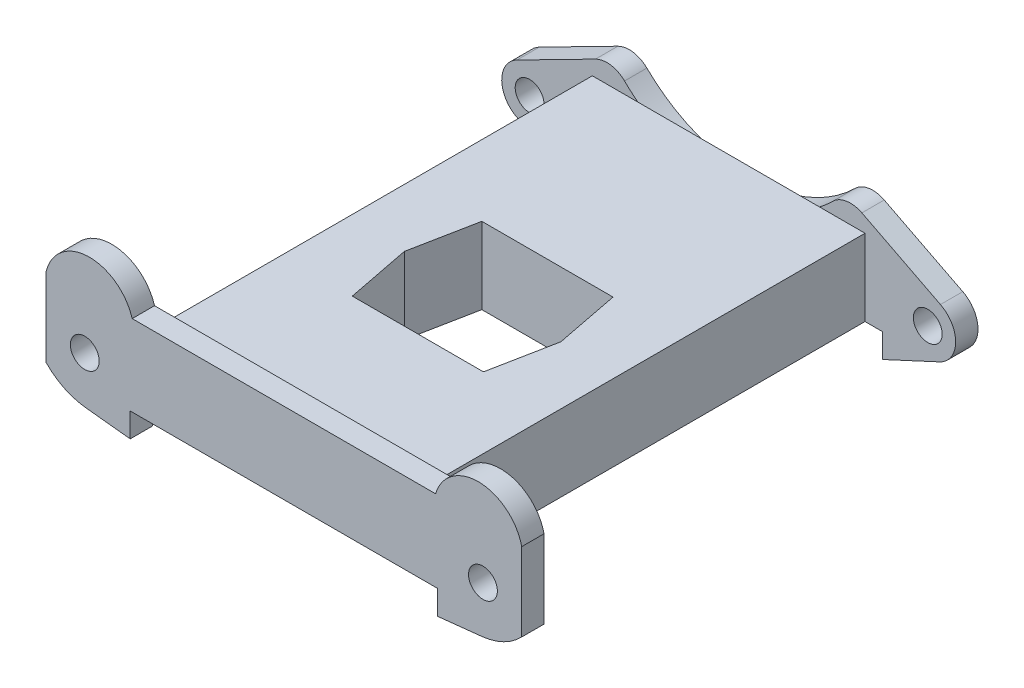
SolidWorks part; units mm, degrees
ref_plane "Front Plane" through (0, 0, 0) normal (0, 0, 1) x (1, 0, 0)
ref_plane "Top Plane" through (0, 0, 0) normal (0, 1, 0) x (1, 0, 0)
ref_plane "Right Plane" through (0, 0, 0) normal (1, 0, 0) x (0, 0, -1)
sketch "Sketch1" plane through (0, 0, 0) normal (0, 1, 0) x (1, 0, 0)
  line L0 (-8.9499, 4.0894) -> (8.9499, 4.0894)
  line L1 (18.6055, -28.829) -> (-18.6055, -28.829)
  line L2 (18.6055, -28.829) -> (18.6055, 28.829)
  line L3 (18.6055, 28.829) -> (-18.6055, 28.829)
  line L4 (-18.6055, -28.829) -> (-18.6055, 28.829)
  line L5 (18.6055, -28.829) -> (-18.6055, 28.829) construction
  line L6 (18.6055, 28.829) -> (-18.6055, -28.829) construction
  line L7 (8.9499, 4.0894) -> (10.6807, -4.7498)
  line L8 (10.6807, -4.7498) -> (8.9499, -13.589)
  line L9 (8.9499, -13.589) -> (-8.9499, -13.589)
  line L10 (-8.9499, -13.589) -> (-10.6807, -4.7498)
  line L11 (-10.6807, -4.7498) -> (-8.9499, 4.0894)
  line L12 (0, 4.0894) -> (0, -13.589) construction
  point P0 (0, 0)
  dimension "D1" = 57.658
  dimension "D2" = 37.211
  dimension "D3" = 21.3614
  dimension "D4" = 17.6784
  dimension "D5" = 15.24
  dimension "D6" = 9.0071
extrude "Boss-Extrude1" add sketch "Sketch1" along normal blind 10.4394
sketch "Sketch2" plane through (0, 0, 28.829) normal (0, 0, 1) x (1, 0, 0)
  line L0 (-20.701, 11.049) -> (20.701, 11.049)
  line L1 (-32.4612, 10.6796) -> (-32.4612, 0)
  line L2 (-20.9677, 0) -> (20.9677, 0)
  line L3 (-27.0496, -2.6515) -> (-20.9677, -3.302)
  line L4 (0, 14.523) -> (0, -4.1487) construction
  line L5 (20.9677, -3.302) -> (20.9677, 0)
  line L6 (-20.9677, -3.302) -> (-20.9677, 0)
  line L7 (27.0496, -2.6515) -> (20.9677, -3.302)
  line L8 (-18.6055, 0) -> (18.6055, 0) construction
  line L9 (32.4612, 10.6796) -> (32.4612, 0)
  arc A0 (-32.4612, 0) -> (-27.0496, -2.6515) centre (-26.1127, 6.1087) ccw
  arc A1 (20.701, 11.049) -> (32.4612, 10.6796) centre (26.5324, 9.3131) cw
  arc A2 (32.4612, 0) -> (27.0496, -2.6515) centre (26.1127, 6.1087) cw
  arc A4 (-20.701, 11.049) -> (-32.4612, 10.6796) centre (-26.5324, 9.3131) ccw
  point P3 (0, 11.049)
  point P7 (0, 0)
  point P13 (0, 11.049)
  point P15 (0, 0)
  point P19 (0, 11.049)
  point P26 (0, 11.049)
  dimension "D5" = 6.0843
  dimension "D8" = 8.8102
  dimension "D1" = 20.9677
  dimension "D2" = 32.4612
  dimension "D3" = 3.302
  dimension "D4" = 11.049
  dimension "D6" = 20.701
  dimension "D7" = 6.1166
  dimension "D9" = 10.6796
extrude "Boss-Extrude2" add sketch "Sketch2" along normal blind 3.048
sketch "Sketch3" plane through (0, 0, -28.829) normal (0, 0, -1) x (-1, 0, 0)
  line L0 (0, 6.223) -> (0, 0) construction
  line L1 (-18.6055, 0) -> (18.6055, 0) construction
  line L2 (18.175, 12.6299) -> (28.8986, 7.1591)
  line L3 (28.7697, 0.3147) -> (20.9677, -3.302)
  line L4 (20.9677, -3.302) -> (20.9677, 0)
  line L5 (20.9677, 0) -> (0, 0)
  line L6 (30.9753, 9.9955) -> (30.9753, -1.3561) construction
  line L7 (9.3185, 13.0048) -> (19.1089, 13.0048) construction
  line L8 (-9.3185, 13.0048) -> (-19.1089, 13.0048) construction
  line L9 (-30.9753, 9.9955) -> (-30.9753, -1.3561) construction
  line L10 (-20.9677, -3.302) -> (-20.9677, 0)
  line L11 (-28.7697, 0.3147) -> (-20.9677, -3.302)
  line L12 (-18.175, 12.6299) -> (-28.8986, 7.1591)
  line L13 (-20.9677, 0) -> (0, 0)
  arc A0 (-14.2133, 12.0244) -> (14.2133, 12.0244) centre (0, 26.5348) ccw
  arc A1 (28.8986, 7.1591) -> (28.7697, 0.3147) centre (27.1687, 3.7683) cw
  arc A2 (14.2133, 12.0244) -> (18.175, 12.6299) centre (16.6152, 9.5724) cw
  arc A3 (-14.2133, 12.0244) -> (-18.175, 12.6299) centre (-16.6152, 9.5724) ccw
  arc A4 (-28.8986, 7.1591) -> (-28.7697, 0.3147) centre (-27.1687, 3.7683) ccw
  dimension "D1" = 13.0048
  dimension "D4" = 30.9753
  dimension "D6" = 8.5995
extrude "Boss-Extrude3" add sketch "Sketch3" along normal blind 3.048
sketch "Sketch5" plane through (0, 0, -31.877) normal (0, 0, -1) x (-1, 0, 0)
  circle A0 centre (-27.1687, 3.7683) radius 1.9685
  circle A1 centre (27.1687, 3.7683) radius 1.9685
  arc A2 (-28.8986, 7.1591) -> (-28.7697, 0.3147) centre (-27.1687, 3.7683) ccw construction
  arc A3 (28.7697, 0.3147) -> (28.8986, 7.1591) centre (27.1687, 3.7683) ccw construction
  dimension "D2" = 3.937
extrude "Cut-Extrude1" cut sketch "Sketch5" against normal through all
sketch "Sketch6" plane through (0, 0, 0) normal (0, -1, 0) x (1, 0, 0)
  line L0 (0, 40.7775) -> (0, -39.818) construction
  line L1 (-20.9677, 31.877) -> (20.9677, 31.877) construction
  circle A0 centre (-10.0076, 24.6507) radius 1.9685
  circle A1 centre (10.0076, 24.6507) radius 1.9685
  circle A2 centre (-10.0076, -16.1417) radius 1.9685
  circle A3 centre (10.0076, -16.1417) radius 1.9685
  dimension "D1" = 3.937
  dimension "D2" = 20.0152
  dimension "D3" = 40.7924
  dimension "D4" = 7.2263
extrude "Cut-Extrude2" cut sketch "Sketch6" against normal blind 5.08
